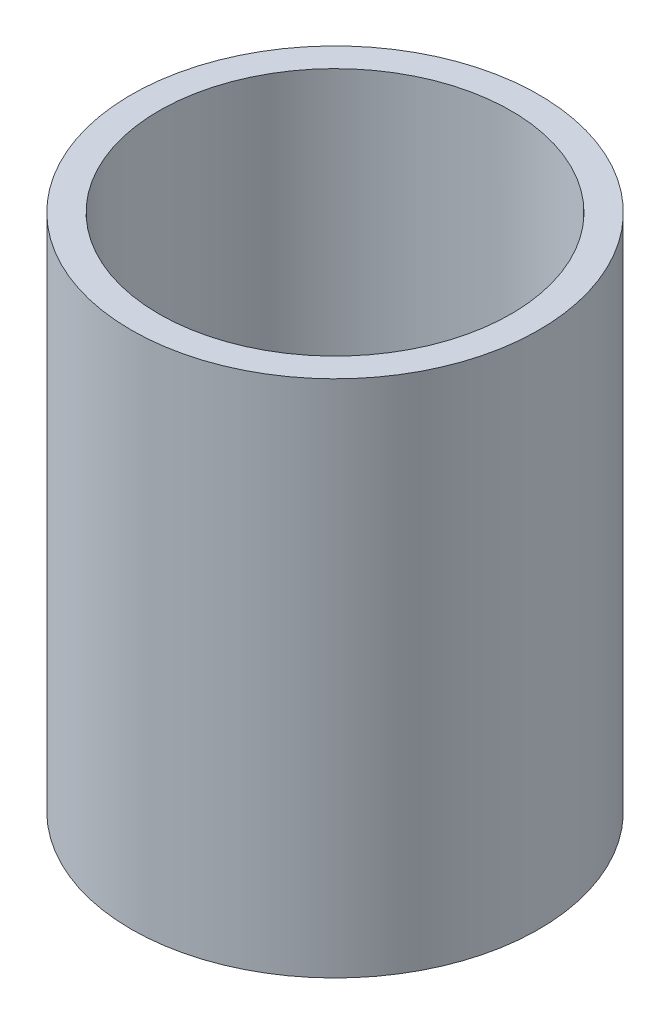
SolidWorks part; units mm, degrees
ref_plane "Front Plane" through (0, 0, 0) normal (0, 0, 1) x (1, 0, 0)
ref_plane "Top Plane" through (0, 0, 0) normal (0, 1, 0) x (1, 0, 0)
ref_plane "Right Plane" through (0, 0, 0) normal (1, 0, 0) x (0, 0, -1)
sketch "Sketch1" plane through (0, 0, 0) normal (0, 1, 0) x (1, 0, 0)
  circle A0 centre (0, 0) radius 11
  circle A1 centre (0, 0) radius 9.5
  dimension "D1" = 22
  dimension "D2" = 19
extrude "Boss-Extrude1" add sketch "Sketch1" along normal mid plane 28
sketch "Sketch2" plane through (0, 0, 0) normal (0, 0, 1) x (1, 0, 0)
  circle A0 centre (0, 0) radius 2
  dimension "D1" = 4
extrude "Cut-Extrude1" cut sketch "Sketch2" against normal blind 28
